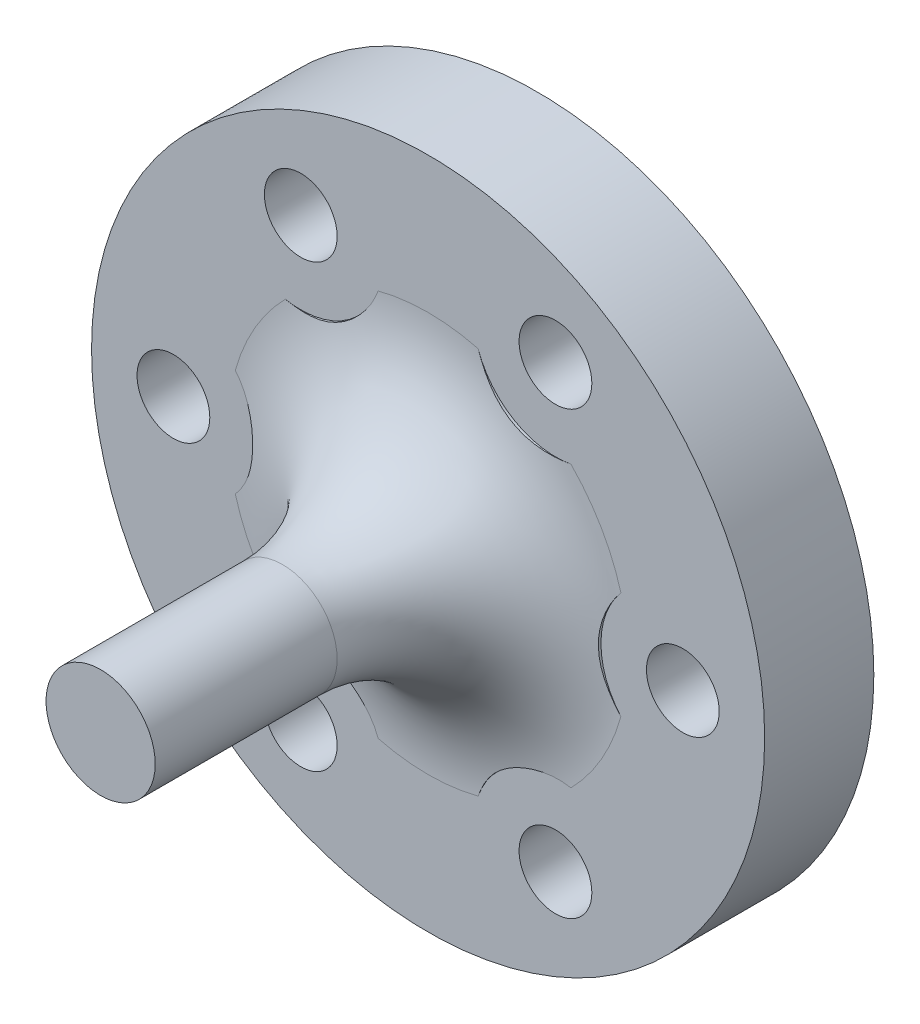
SolidWorks part; units mm, degrees
ref_plane "Front Plane" through (0, 0, 0) normal (0, 0, 1) x (1, 0, 0)
ref_plane "Top Plane" through (0, 0, 0) normal (0, 1, 0) x (1, 0, 0)
ref_plane "Right Plane" through (0, 0, 0) normal (1, 0, 0) x (0, 0, -1)
sketch "Sketch1" plane through (0, 0, 0) normal (0, 0, 1) x (1, 0, 0)
  circle A0 centre (0, 0) radius 18.5
  dimension "D1" = 37
extrude "Boss-Extrude1" add sketch "Sketch1" along normal blind 6
sketch "Sketch3" plane through (0, 0, 6) normal (0, 0, 1) x (1, 0, 0)
  circle A0 centre (-14, 0) radius 2
  circle A1 centre (-7, 12.1244) radius 2
  circle A2 centre (7, 12.1244) radius 2
  circle A3 centre (14, 0) radius 2
  circle A4 centre (7, -12.1244) radius 2
  circle A5 centre (-7, -12.1244) radius 2
  circle A6 centre (0, 0) radius 14 construction
  point P16 (0, 0)
  dimension "D1" = 4
  dimension "D4" = 28
  dimension "D5" = 60
  dimension "D3" = 6
extrude "Cut-Extrude1" cut sketch "Sketch3" against normal up to surface (6 mm away) up to face at (18.5, 0, 0)
ref_plane "Plane1" through (0, 0, 24) normal (0, 0, 1) x (1, 0, 0)
sketch "Sketch4" plane through (0, 0, 24) normal (0, 0, 1) x (1, 0, 0)
  circle A1 centre (0, 0) radius 3
  dimension "D1" = 6
sketch "Sketch7" plane through (0, 0, 24) normal (0, 0, 1) x (1, 0, 0)
  circle A0 centre (0, 0) radius 3
  dimension "D1" = 6
extrude "Boss-Extrude4" add sketch "Sketch7" against normal up to surface (18 mm away) up to face at (-12, 0, 6)
fillet "Fillet3" radius 8 1 edges at (3, 0, 6)
sketch "Sketch8" plane through (0, 0, 6) normal (0, 0, 1) x (1, 0, 0)
  circle A0 centre (-14, 0) radius 4.5
  circle A1 centre (0, 0) radius 14 construction
  circle A2 centre (-7, 12.1244) radius 4.5
  circle A3 centre (7, 12.1244) radius 4.5
  circle A4 centre (14, 0) radius 4.5
  circle A5 centre (7, -12.1244) radius 4.5
  circle A6 centre (-7, -12.1244) radius 4.5
  point P7 (0, 0)
  point P18 (0, 0)
  dimension "D1" = 9
  dimension "D2" = 28
  dimension "D4" = 60
  dimension "D3" = 6
extrude "Cut-Extrude2" cut sketch "Sketch8" along normal blind 10
